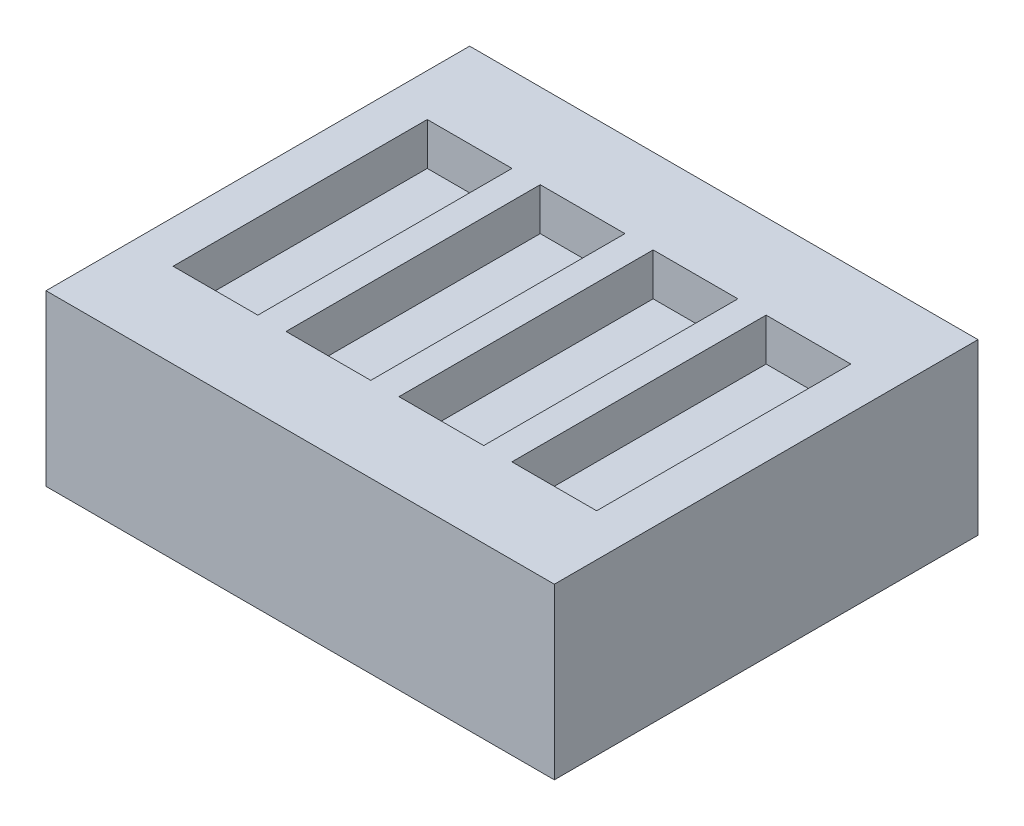
SolidWorks part; units mm, degrees
ref_plane "Front Plane" through (0, 0, 0) normal (0, 0, 1) x (1, 0, 0)
ref_plane "Top Plane" through (0, 0, 0) normal (0, 1, 0) x (1, 0, 0)
ref_plane "Right Plane" through (0, 0, 0) normal (1, 0, 0) x (0, 0, -1)
sketch "Sketch1" plane through (0, 0, 0) normal (0, 1, 0) x (1, 0, 0)
  line L1 (0, 0) -> (6, 0)
  line L2 (0, 0) -> (0, 5)
  line L3 (0, 5) -> (6, 5)
  line L4 (6, 0) -> (6, 5)
extrude "Boss-Extrude1" add sketch "Sketch1" along normal blind 2
sketch "Sketch2" plane through (0, 2, 0) normal (0, 1, 0) x (1, 0, 0)
  line L0 (6, 5) -> (0, 5) construction
  line L1 (0.5, 4) -> (1.5, 4)
  line L2 (0.5, 4) -> (0.5, 1)
  line L3 (0.5, 1) -> (1.5, 1)
  line L4 (1.5, 4) -> (1.5, 1)
  line L5 (0, 0) -> (6, 0) construction
  line L6 (0, 5) -> (0, 0) construction
  line L7 (5.5, 5) -> (5.5, 0) construction
  line L8 (6, 0) -> (6, 5) construction
  line L9 (1.833, 4) -> (1.833, 1)
  line L10 (1.833, 4) -> (2.833, 4)
  line L11 (2.833, 4) -> (2.833, 1)
  line L12 (1.833, 1) -> (2.833, 1)
  line L13 (3.166, 4) -> (3.166, 1)
  line L14 (3.166, 4) -> (4.166, 4)
  line L15 (4.166, 4) -> (4.166, 1)
  line L16 (3.166, 1) -> (4.166, 1)
  line L17 (4.499, 4) -> (4.499, 1)
  line L18 (4.499, 4) -> (5.499, 4)
  line L19 (5.499, 4) -> (5.499, 1)
  line L20 (4.499, 1) -> (5.499, 1)
  dimension "D1" = 1
  dimension "D2" = 1
  dimension "D3" = 0.5
  dimension "D4" = 0.5
  dimension "D5" = 4
extrude "Cut-Extrude1" cut sketch "Sketch2" against normal blind 0.5 contours L2 L1 L4 L3 | L9 L12 L11 L10 | L13 L16 L15 L14 | L17 L20 L19 L18
sketch "Sketch3" plane through (0, 1.5, 0) normal (0, 1, 0) x (1, 0, 0)
  line L0 (2.833, 4) -> (2.833, 1) construction
  line L1 (1.933, 2.1) -> (2.733, 2.1)
  line L2 (1.933, 2.1) -> (1.933, 1.1)
  line L3 (1.933, 1.1) -> (2.733, 1.1)
  line L4 (2.733, 2.1) -> (2.733, 1.1)
  line L5 (1.833, 4) -> (1.833, 1) construction
  line L6 (1.833, 1) -> (2.833, 1) construction
  line L7 (1.5, 1) -> (1.833, 1) construction
  line L8 (1.833, 1) -> (1.6665, 1) construction
  line L9 (1.6665, 1) -> (1.6665, 1.5055) construction
  line L10 (2.833, 1) -> (3.166, 1) construction
  line L11 (3.166, 1) -> (2.9995, 1) construction
  line L12 (2.9995, 1) -> (2.9995, 1.5055) construction
  line L13 (1.4, 1.1) -> (0.6, 1.1)
  line L14 (0.6, 2.1) -> (0.6, 1.1)
  line L15 (1.4, 2.1) -> (0.6, 2.1)
  line L16 (1.4, 2.1) -> (1.4, 1.1)
  line L17 (4.066, 1.1) -> (3.266, 1.1)
  line L18 (3.266, 2.1) -> (3.266, 1.1)
  line L19 (4.066, 2.1) -> (3.266, 2.1)
  line L20 (4.066, 2.1) -> (4.066, 1.1)
  line L21 (4.599, 2.1) -> (4.599, 1.1)
  line L22 (4.599, 2.1) -> (5.399, 2.1)
  line L23 (5.399, 2.1) -> (5.399, 1.1)
  line L24 (4.599, 1.1) -> (5.399, 1.1)
  dimension "D1" = 0.1
  dimension "D2" = 0.1
  dimension "D3" = 0.1
  dimension "D4" = 1
